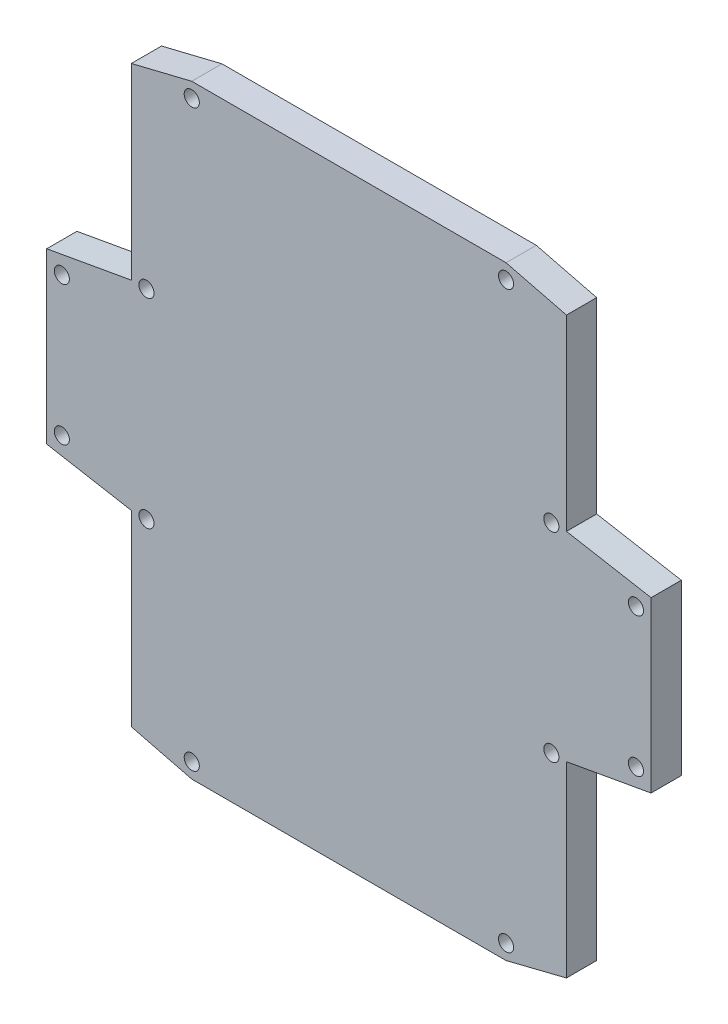
SolidWorks part; units mm, degrees
ref_plane "Front Plane" through (0, 0, 0) normal (0, 0, 1) x (1, 0, 0)
ref_plane "Top Plane" through (0, 0, 0) normal (0, 1, 0) x (1, 0, 0)
ref_plane "Right Plane" through (0, 0, 0) normal (1, 0, 0) x (0, 0, -1)
sketch "Sketch1" plane through (0, 0, 0) normal (0, 0, 1) x (1, 0, 0)
  line L1 (-52, 100) -> (52, 100)
  line L2 (-100, 28) -> (-100, -28)
  line L3 (-52, -100) -> (52, -100)
  line L4 (100, 28) -> (100, -28)
  line L5 (-72, 72) -> (72, -72) construction
  line L6 (-72, -72) -> (72, 72) construction
  line L7 (-72, -33) -> (-72, -95)
  line L9 (-72, 33) -> (-72, 95.1074)
  line L10 (-72, 33) -> (-100, 28)
  line L12 (72, 95) -> (72, 33)
  line L14 (72, -33) -> (72, -95)
  line L15 (72, 33) -> (100, 28)
  line L16 (-72, -33) -> (-100, -28)
  line L17 (72, -33) -> (100, -28)
  line L18 (-72, 95.1074) -> (-52, 100)
  line L19 (72, 95) -> (52, 100)
  line L20 (-72, -95) -> (-52, -100)
  line L21 (52, -100) -> (72, -95)
  line L22 (-52, 100) -> (-52, -100) construction
  line L23 (52, 100) -> (52, -100) construction
  point P0 (0, 0)
  dimension "D8" = 28
  dimension "D5" = 20
  dimension "D3" = 28
  dimension "D4" = 28
  dimension "D6" = 20
  dimension "D7" = 20
  dimension "D9" = 144
  dimension "D19" = 144
  dimension "D21" = 20
extrude "Boss-Extrude2" add sketch "Sketch1" along normal blind 15
sketch "Sketch2" plane through (0, 0, 15) normal (0, 0, 1) x (1, 0, 0)
  line L0 (-52, 100) -> (-52, -100) construction
  line L1 (52, 100) -> (52, -100) construction
  line L2 (-71, 95.352) -> (-68, 95.352) construction
  line L3 (-100, 28) -> (100, 28) construction
  line L4 (-100, -28) -> (100, -28) construction
  line L5 (71, 95.25) -> (71, -95.25) construction
  line L6 (72, 95) -> (52, 100) construction
  line L7 (52, -100) -> (72, -95) construction
  line L8 (72, 33) -> (72, 95) construction
  line L9 (-71, -95.25) -> (-68, -95.25) construction
  line L10 (-71, 95.352) -> (-71, -95.25) construction
  line L11 (-52, 100) -> (-72, 95.1074) construction
  line L12 (-72, -95) -> (-52, -100) construction
  line L13 (-72, 95.1074) -> (-72, 33) construction
  line L14 (-68, 96.0859) -> (-68, -96) construction
  line L15 (68, -96) -> (68, 96) construction
  line L16 (99, 28.1786) -> (99, -28.1786) construction
  line L17 (100, 28) -> (72, 33) construction
  line L18 (72, -33) -> (100, -28) construction
  line L19 (96, 28.7143) -> (96, -28.7143) construction
  line L20 (-99, -29.8888) -> (-99, 28.1786) construction
  line L21 (-72, 33) -> (-100, 28) construction
  line L22 (-71, 90.352) -> (-68, 90.352)
  line L23 (-96, 28.7143) -> (-96, -28.7143) construction
  line L24 (-100, -28) -> (-72, -33) construction
  line L25 (100, -28) -> (100, 28) construction
  line L26 (-100, 28) -> (-100, -28) construction
  line L27 (-68, 90.352) -> (-68, 70.352)
  line L28 (-52, -100) -> (52, -100) construction
  line L29 (-68, 70.352) -> (-71, 70.352)
  line L30 (-71, 70.352) -> (-71, 90.352)
  line L31 (-71, 33) -> (-68, 33)
  line L32 (-68, 33) -> (-68, 53)
  line L33 (-68, 53) -> (-71, 53)
  line L34 (-71, 53) -> (-71, 33)
  dimension "D1" = 1
  dimension "D2" = 1
  dimension "D3" = 3
  dimension "D4" = 3
  dimension "D5" = 1
  dimension "D6" = 3
  dimension "D7" = 1
  dimension "D8" = 3
  dimension "D9" = 190.602
  dimension "D10" = 200
  dimension "D11" = 192.0859
  dimension "D12" = 103.746
  dimension "D13" = 104.036
  dimension "D14" = 3
  dimension "D15" = 3
  dimension "D16" = 3
  dimension "D17" = 3.0923
  dimension "D18" = 3.0885
  dimension "D19" = 0.75
  dimension "D20" = 0.7339
  dimension "D21" = 56
  dimension "D22" = 67.352
  dimension "D23" = 67.25
  dimension "D24" = 5
  dimension "D25" = 20
  dimension "D26" = 5
  dimension "D27" = 20
extrude "Cut-Extrude2" cut sketch "Sketch2" against normal blind 10
sketch "Sketch4" plane through (0, 0, 15) normal (0, 0, 1) x (1, 0, 0)
  line L0 (-71, 90.352) -> (-68, 90.352)
  line L1 (-68, 90.352) -> (-68, 70.352)
  line L2 (-68, 70.352) -> (-69.5, 70.352)
  line L3 (-71, 70.352) -> (-68, 70.352) construction
  line L4 (-69.5, 70.352) -> (-71, 70.352)
  line L5 (-71, 70.352) -> (-71, 90.352)
  line L6 (-71, 53) -> (-68, 53)
  line L7 (-68, 53) -> (-68, 33)
  line L8 (-68, 33) -> (-71, 33)
  line L9 (-71, 33) -> (-71, 53)
extrude "Boss-Extrude5" add sketch "Sketch4" against normal blind 10
sketch "Sketch5" plane through (0, 0, 15) normal (0, 0, 1) x (1, 0, 0)
  line L0 (-72, 95.1074) -> (-72, 33)
  line L1 (-72, 33) -> (-100, 28)
  line L2 (-100, 28) -> (-100, -28)
  line L3 (-100, -28) -> (-72, -33)
  line L4 (-72, -33) -> (-72, -95)
  line L5 (-72, -95) -> (-52, -100)
  line L6 (-72, -95) -> (-52, -100) construction
  line L7 (-52, -100) -> (52, -100)
  line L8 (52, -100) -> (72, -95)
  line L9 (72, -95) -> (72, -33)
  line L10 (72, -33) -> (100, -28)
  line L11 (100, -28) -> (100, 28)
  line L12 (100, 28) -> (72, 33)
  line L13 (72, 33) -> (72, 95)
  line L14 (72, 95) -> (52, 100)
  line L15 (52, 100) -> (-52, 100)
  line L16 (-52, 100) -> (-72, 95.1074)
  line L17 (-52, -100) -> (52, -100) construction
  point P36 (0, -100)
extrude "Cut-Extrude3" cut sketch "Sketch5" against normal blind 5
sketch "Sketch6" plane through (0, 0, 10) normal (0, 0, 1) x (1, 0, 0)
  line L0 (-52, 100) -> (-52, -100) construction
  line L1 (-72, 95.1074) -> (-52, 95.1074) construction
  line L2 (-72, -95) -> (-52, -95) construction
  line L3 (-72, -33) -> (-52, -33) construction
  line L4 (-72, 33) -> (-52, 33) construction
  line L5 (-100, 28) -> (-52, 28) construction
  line L6 (-100, -28) -> (-52, -28) construction
  line L7 (-72, 33) -> (-72, -33) construction
  line L8 (-67, 95.1074) -> (-67, -95) construction
  line L13 (-95, 28) -> (-95, -28) construction
  line L14 (-100, 28) -> (-100, -28) construction
  line L15 (-100, 23) -> (-52, 23) construction
  line L16 (-100, -23) -> (-52, -23) construction
  line L17 (0, 100) -> (0, -100) construction
  line L18 (52, 100) -> (-52, 100) construction
  line L19 (-52, -100) -> (52, -100) construction
  line L20 (100, -23) -> (52, -23) construction
  line L21 (100, 23) -> (52, 23) construction
  line L22 (95, 28) -> (95, -28) construction
  line L23 (67, 95.1074) -> (67, -95) construction
  line L24 (72, 33) -> (72, -33) construction
  line L25 (100, -28) -> (52, -28) construction
  line L26 (100, 28) -> (52, 28) construction
  line L27 (72, 33) -> (52, 33) construction
  line L28 (72, -33) -> (52, -33) construction
  line L29 (72, -95) -> (52, -95) construction
  line L30 (72, 95.1074) -> (52, 95.1074) construction
  line L31 (52, 100) -> (52, -100) construction
  circle A0 centre (-52, 95.1074) radius 2.5
  circle A1 centre (-52, -95) radius 2.5
  circle A2 centre (-67, -33) radius 2.5
  circle A3 centre (-67, 33) radius 2.5
  circle A4 centre (-95, 23) radius 2.5
  circle A5 centre (-95, -23) radius 2.5
  circle A7 centre (95, -23) radius 2.5
  circle A8 centre (95, 23) radius 2.5
  circle A9 centre (67, 33) radius 2.5
  circle A10 centre (67, -33) radius 2.5
  circle A11 centre (52, -95) radius 2.5
  circle A12 centre (52, 95.1074) radius 2.5
  dimension "D2" = 5
  dimension "D3" = 5
  dimension "D4" = 5
  dimension "D5" = 5
  dimension "D9" = 5
  dimension "D10" = 5
  dimension "D1" = 5
  dimension "D6" = 5
  dimension "D7" = 5
  dimension "D8" = 5
extrude "Cut-Extrude4" cut sketch "Sketch6" against normal blind 6
